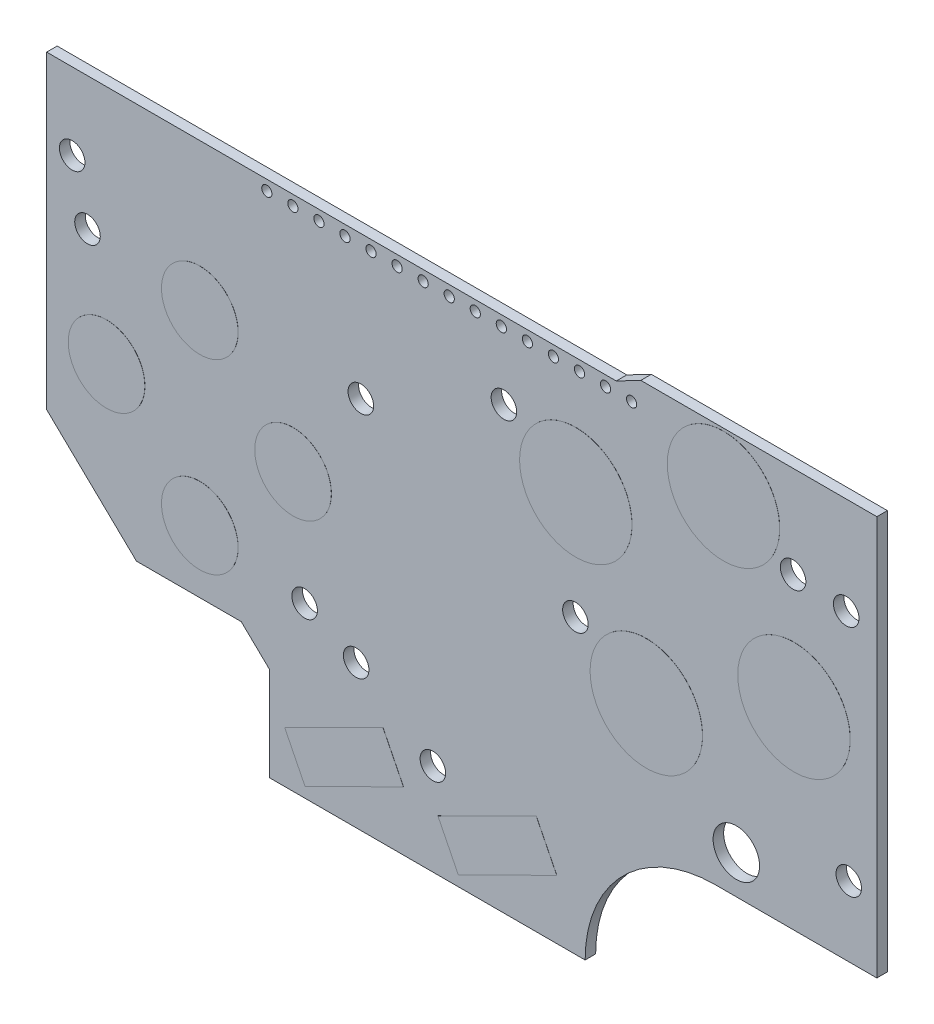
SolidWorks part; units mm, degrees
ref_plane "Front Plane" through (0, 0, 0) normal (0, 0, 1) x (1, 0, 0)
ref_plane "Top Plane" through (0, 0, 0) normal (0, 1, 0) x (1, 0, 0)
ref_plane "Right Plane" through (0, 0, 0) normal (1, 0, 0) x (0, 0, -1)
sketch "Sketch1" plane through (0, 0, 0) normal (0, 0, 1) x (1, 0, 0)
  line L0 (0, 0) -> (55.75, 0)
  line L1 (55.75, 0) -> (58.15, 1.25)
  line L2 (58.15, 1.25) -> (81.25, 1.25)
  line L3 (81.25, 1.25) -> (81.25, -37.85)
  line L4 (81.25, -37.85) -> (65.45, -37.85)
  line L5 (0, 0) -> (0, -30.3)
  line L6 (0, -30.3) -> (8.7926, -38.75)
  line L7 (8.7926, -38.75) -> (19.0426, -38.75)
  line L8 (19.0426, -38.75) -> (21.8, -41.4)
  line L9 (21.8, -41.4) -> (21.8, -50.6)
  line L10 (21.8, -50.6) -> (52.7, -50.6)
  arc A0 (65.45, -37.85) -> (52.7, -50.6) centre (65.45, -50.6) ccw
  dimension "D1" = 39.1
  dimension "D2" = 38.75
  dimension "D3" = 50.6
  dimension "D4" = 30.9
  dimension "D5" = 81.25
  dimension "D6" = 25.5
  dimension "D7" = 23.1
  dimension "D8" = 1.25
  dimension "D9" = 21.8
  dimension "D10" = 10.25
  dimension "D11" = 30.3
  dimension "D12" = 9.2
extrude "Boss-Extrude1" add sketch "Sketch1" along normal mid plane 1.03
sketch "Sketch3" plane through (0, 0, 0) normal (0, 0, 1) x (1, 0, 0)
  line L9 (15, -14.375) -> (15, -32.625) construction
  line L10 (24.125, -23.5) -> (5.875, -23.5) construction
  circle A4 centre (15, -14.375) radius 3.75
  circle A5 centre (15, -32.625) radius 3.75
  circle A6 centre (24.125, -23.5) radius 3.75
  circle A7 centre (5.875, -23.5) radius 3.75
  point P23 (15, -23.5)
  point P24 (15, -23.5)
  dimension "D3" = 14.375
  dimension "D10" = 7.5
  dimension "D2" = 5.875
  dimension "D9" = 18.25
sketch "Sketch2" plane through (0, 0, 0.515) normal (0, 0, 1) x (1, 0, 0)
  line L0 (66.25, -4.5) -> (51.7962, -11.4086) construction
  line L1 (66.25, -4.5) -> (73.15, -18.9357) construction
  line L2 (51.7962, -11.4086) -> (58.6962, -25.8443) construction
  line L3 (73.15, -18.9357) -> (58.6962, -25.8443) construction
  line L4 (81.25, -37.85) -> (81.25, 1.25) construction
  line L8 (81.25, 1.25) -> (58.15, 1.25) construction
  circle A0 centre (66.25, -4.5) radius 5.5
  circle A1 centre (73.15, -18.9357) radius 5.5
  circle A2 centre (58.6962, -25.8443) radius 5.5
  circle A3 centre (51.7962, -11.4086) radius 5.5
  dimension "D1" = 16.02
  dimension "D3" = 11
  dimension "D2" = 16
  dimension "D4" = 8.1
  dimension "D5" = 15
  dimension "D6" = 5.75
extrude "Boss-Extrude2" add sketch "Sketch2" along normal blind 0.01
extrude "Boss-Extrude5" add sketch "Sketch3" along normal through all
sketch "Sketch5" plane through (0, 0, 0.515) normal (0, 0, 1) x (1, 0, 0)
  line L0 (32.9189, -40.7735) -> (23.3, -45.5735)
  line L1 (32.9189, -40.7735) -> (34.9282, -44.8)
  line L2 (23.3, -45.5735) -> (25.3093, -49.6)
  line L3 (34.9282, -44.8) -> (25.3093, -49.6)
  line L4 (38.3, -45.5735) -> (40.3093, -49.6)
  line L5 (38.3, -45.5735) -> (47.9189, -40.7735)
  line L6 (40.3093, -49.6) -> (49.9282, -44.8)
  line L7 (47.9189, -40.7735) -> (49.9282, -44.8)
  line L8 (21.8, -41.4) -> (21.8, -50.6) construction
  line L9 (21.8, -50.6) -> (52.7, -50.6) construction
  dimension "D1" = 10.75
  dimension "D2" = 4.5
  dimension "D3" = 1.5
  dimension "D4" = 1
  dimension "D5" = 16.5
  dimension "D6" = 5.8
extrude "Boss-Extrude6" add sketch "Sketch5" along normal blind 0.01
sketch "Sketch6" plane through (0, 0, 0.515) normal (0, 0, 1) x (1, 0, 0)
  line L0 (81.25, -37.85) -> (81.25, 1.25) construction
  line L1 (55.75, 0) -> (0, 0) construction
  circle A0 centre (57.25, -1) radius 0.5
  dimension "D1" = 1
  dimension "D2" = 24
  dimension "D3" = 1
extrude "Cut-Extrude1" cut sketch "Sketch6" against normal through all
pattern_linear "LPattern1" count 15 spacing 2.55 along (-1, 0, 0) of "Cut-Extrude1"
sketch "Sketch7" plane through (0, 0, 0.515) normal (0, 0, 1) x (1, 0, 0)
  line L0 (65.45, -37.85) -> (81.25, -37.85) construction
  line L1 (81.25, -37.85) -> (81.25, 1.25) construction
  circle A0 centre (67.5, -34.1) radius 2.275
  circle A1 centre (78.5, -31) radius 1.25
  dimension "D1" = 4.55
  dimension "D4" = 2.5
  dimension "D2" = 3.75
  dimension "D3" = 13.75
  dimension "D5" = 2.75
  dimension "D6" = 6.85
extrude "Cut-Extrude2" cut sketch "Sketch7" against normal through all
sketch "Sketch8" plane through (0, 0, 0.515) normal (0, 0, 1) x (1, 0, 0)
  line L0 (81.25, -37.85) -> (81.25, 1.25) construction
  line L1 (81.25, 1.25) -> (58.15, 1.25) construction
  circle A0 centre (78.25, -8.25) radius 1.25
  dimension "D1" = 2.5
  dimension "D2" = 3
  dimension "D3" = 9.5
extrude "Cut-Extrude3" cut sketch "Sketch8" against normal through all
sketch "Sketch9" plane through (0, 0, 0.515) normal (0, 0, 1) x (1, 0, 0)
  line L0 (81.25, -37.85) -> (81.25, 1.25) construction
  line L1 (81.25, 1.25) -> (58.15, 1.25) construction
  circle A0 centre (73.05, -7.75) radius 1.25
  dimension "D1" = 2.5
  dimension "D2" = 8.2
  dimension "D3" = 9
extrude "Cut-Extrude4" cut sketch "Sketch9" against normal through all
sketch "Sketch10" plane through (0, 0, 0.515) normal (0, 0, 1) x (1, 0, 0)
  line L0 (81.25, -37.85) -> (81.25, 1.25) construction
  line L1 (55.75, 0) -> (0, 0) construction
  circle A0 centre (44.75, -7.5) radius 1.25
  dimension "D1" = 2.5
  dimension "D2" = 36.5
  dimension "D3" = 7.5
extrude "Cut-Extrude5" cut sketch "Sketch10" against normal through all
sketch "Sketch11" plane through (0, 0, 0.515) normal (0, 0, 1) x (1, 0, 0)
  line L0 (81.25, -37.85) -> (81.25, 1.25) construction
  line L1 (55.75, 0) -> (0, 0) construction
  circle A0 centre (51.75, -22) radius 1.25
  dimension "D1" = 2.5
  dimension "D2" = 29.5
  dimension "D3" = 22
extrude "Cut-Extrude6" cut sketch "Sketch11" against normal through all
sketch "Sketch12" plane through (0, 0, 0.515) normal (0, 0, 1) x (1, 0, 0)
  line L0 (21.8, -50.6) -> (52.7, -50.6) construction
  line L1 (21.8, -41.4) -> (21.8, -50.6) construction
  circle A0 centre (37.8, -41.6) radius 1.25
  dimension "D1" = 2.5
  dimension "D2" = 9
  dimension "D3" = 16
extrude "Cut-Extrude7" cut sketch "Sketch12" against normal through all
sketch "Sketch13" plane through (0, 0, 0.515) normal (0, 0, 1) x (1, 0, 0)
  line L1 (21.8, -50.6) -> (52.7, -50.6) construction
  circle A0 centre (30.2926, -36.6) radius 1.25
  dimension "D1" = 21.5
  dimension "D3" = 2.5
  dimension "D2" = 14
extrude "Cut-Extrude8" cut sketch "Sketch13" against normal through all
sketch "Sketch14" plane through (0, 0, 0.515) normal (0, 0, 1) x (1, 0, 0)
  line L0 (81.25, -37.85) -> (81.25, 1.25) construction
  line L1 (21.8, -50.6) -> (52.7, -50.6) construction
  circle A0 centre (25.25, -34.1) radius 1.25
  dimension "D1" = 2.5
  dimension "D2" = 56
  dimension "D3" = 16.5
extrude "Cut-Extrude9" cut sketch "Sketch14" against normal through all
sketch "Sketch15" plane through (0, 0, 0.515) normal (0, 0, 1) x (1, 0, 0)
  line L0 (81.25, -37.85) -> (81.25, 1.25) construction
  line L1 (55.75, 0) -> (0, 0) construction
  circle A0 centre (30.75, -14) radius 1.25
  dimension "D1" = 2.5
  dimension "D2" = 50.5
  dimension "D3" = 14
extrude "Cut-Extrude10" cut sketch "Sketch15" against normal through all
sketch "Sketch16" plane through (0, 0, 0.515) normal (0, 0, 1) x (1, 0, 0)
  line L0 (55.75, 0) -> (0, 0) construction
  line L1 (0, 0) -> (0, -30.3) construction
  circle A0 centre (2.5, -7.5) radius 1.25
  dimension "D1" = 2.5
  dimension "D2" = 7.5
  dimension "D3" = 2.5
extrude "Cut-Extrude11" cut sketch "Sketch16" against normal through all
sketch "Sketch17" plane through (0, 0, 0.515) normal (0, 0, 1) x (1, 0, 0)
  line L0 (55.75, 0) -> (0, 0) construction
  line L1 (0, 0) -> (0, -30.3) construction
  circle A0 centre (4, -13) radius 1.25
  dimension "D1" = 2.5
  dimension "D2" = 13
  dimension "D3" = 4
extrude "Cut-Extrude12" cut sketch "Sketch17" against normal through all
